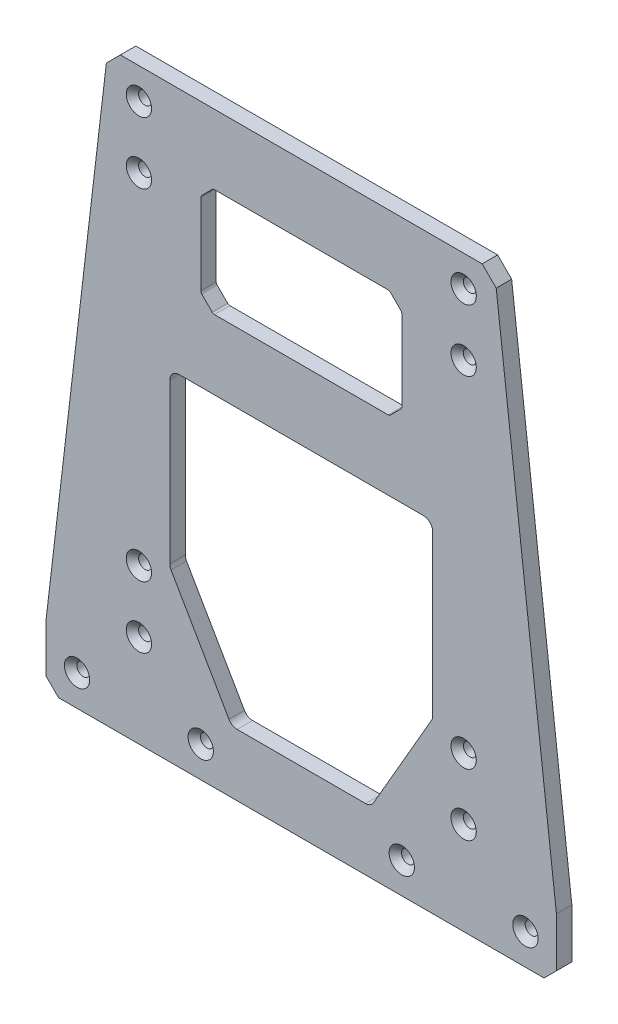
SolidWorks part; units mm, degrees
ref_plane "前视基准面" through (0, 0, 0) normal (0, 0, 1) x (1, 0, 0)
ref_plane "上视基准面" through (0, 0, 0) normal (0, 1, 0) x (1, 0, 0)
ref_plane "右视基准面" through (0, 0, 0) normal (1, 0, 0) x (0, 0, -1)
sketch "草图1" plane through (0, 0, 0) normal (0, 0, 1) x (1, 0, 0)
  line L0 (-82.5, -150) -> (82.5, -150)
  line L2 (62.5, 40) -> (-62.5, 40)
  line L4 (-82.5, -150) -> (-82.5, -130)
  line L5 (-82.5, -130) -> (-62.5, 40)
  line L6 (82.5, -150) -> (82.5, -130)
  line L7 (82.5, -130) -> (62.5, 40)
  line L9 (42.5, -130) -> (-42.5, -130)
  line L10 (42.5, -130) -> (42.5, -40)
  line L11 (42.5, -40) -> (-42.5, -40)
  line L12 (-42.5, -130) -> (-42.5, -40)
  line L13 (42.5, -130) -> (-42.5, -40) construction
  line L14 (42.5, -40) -> (-42.5, -130) construction
  point P2 (0, 40)
  point P5 (0, -150)
  point P9 (0, -85)
  dimension "D1" = 150
  dimension "D2" = 40
  dimension "D3" = 20
  dimension "D4" = 125
  dimension "D5" = 20
  dimension "D6" = 85
  dimension "D7" = 40
  dimension "D8" = 20
extrude "凸台-拉伸1" add sketch "草图1" along normal mid plane 5
chamfer "倒角1" distance 20 angle 60 2 edges at (42.5, -130, 0) (-42.5, -130, 0)
sketch "草图2" plane through (0, 0, 2.5) normal (0, 0, 1) x (1, 0, 0)
  line L0 (-52.5, 30) -> (-52.5, 10) construction
  line L1 (-52.5, 10) -> (-52.5, -100) construction
  line L2 (-52.5, -100) -> (-52.5, -120) construction
  line L3 (-52.5, -120) -> (-52.5, -140) construction
  line L4 (-32.5, -140) -> (-72.5, -140) construction
  line L5 (-82.5, -150) -> (82.5, -150) construction
  line L7 (0, -130) -> (0, 40) construction
  line L8 (-22.5, -130) -> (22.5, -130) construction
  line L9 (62.5, 40) -> (-62.5, 40) construction
  circle A0 centre (-72.5, -140) radius 2.1
  circle A1 centre (-32.5, -140) radius 2.1
  circle A2 centre (-52.5, 30) radius 2.1
  circle A3 centre (-52.5, 10) radius 2.1
  circle A4 centre (-52.5, -100) radius 2.1
  circle A5 centre (-52.5, -120) radius 2.1
  circle A6 centre (52.5, 30) radius 2.1
  circle A7 centre (52.5, 10) radius 2.1
  circle A8 centre (52.5, -100) radius 2.1
  circle A9 centre (52.5, -120) radius 2.1
  circle A10 centre (32.5, -140) radius 2.1
  circle A11 centre (72.5, -140) radius 2.1
  point P17 (-52.5, -140)
  dimension "D1" = 10
  dimension "D3" = 10
  dimension "D4" = 4.2
  dimension "D6" = 10
  dimension "D2" = 40
  dimension "D5" = 20
  dimension "D7" = 20
  dimension "D8" = 20
extrude "切除-拉伸1" cut sketch "草图2" against normal through all
fillet "圆角1" radius 3 6 edges at (22.5, -130, 0) (42.5, -95.359, 0) (-42.5, -95.359, 0) (-22.5, -130, 0) (42.5, -40, 0) (-42.5, -40, 0)
chamfer "倒角2" distance 4 angle 45 4 edges at (82.5, -150, 0) (-82.5, -150, 0) (62.5, 40, 0) (-62.5, 40, 0)
chamfer "倒角3" distance 2 angle 45 12 edges at (-50.4, 30, 2.5) (-50.4, 10, 2.5) (50.4, 30, 2.5) (50.4, 10, 2.5) (70.4, -140, 2.5) (50.4, -100, 2.5) (50.4, -120, 2.5) (30.4, -140, 2.5) (-30.4, -140, 2.5) (-50.4, -100, 2.5) (-50.4, -120, 2.5) (-70.4, -140, 2.5)
sketch "草图4" plane through (0, 0, -2.5) normal (0, 0, -1) x (-1, 0, 0)
  line L0 (0, -40) -> (0, 40) construction
  line L1 (0, -17.5) -> (-32.5, -17.5)
  line L3 (0, 17.5) -> (-32.5, 17.5)
  line L4 (-32.5, -17.5) -> (-32.5, 17.5)
  line L5 (0, -17.5) -> (-32.5, 17.5) construction
  line L6 (0, 17.5) -> (-32.5, -17.5) construction
  line L11 (-39.5, -40) -> (39.5, -40) construction
  line L12 (-58.5, 40) -> (58.5, 40) construction
  line L13 (0, 17.5) -> (32.5, 17.5)
  line L14 (32.5, -17.5) -> (32.5, 17.5)
  line L15 (0, -17.5) -> (32.5, -17.5)
  circle A0 centre (-52.5, 10) radius 2.1 construction
  point P0 (-16.25, 0)
  point P20 (0, 0)
  dimension "D2" = 20
  dimension "D3" = 35
extrude "切除-拉伸3" cut sketch "草图4" against normal through all
chamfer "倒角4" distance 4 angle 45 4 edges at (-32.5, -17.5, 0) (32.5, -17.5, 0) (32.5, 17.5, 0) (-32.5, 17.5, 0)
fillet "圆角3" radius 1 8 edges at (32.5, 13.5, 0) (32.5, -13.5, 0) (28.5, -17.5, 0) (28.5, 17.5, 0) (-32.5, 13.5, 0) (-32.5, -13.5, 0) (-28.5, -17.5, 0) (-28.5, 17.5, 0)
